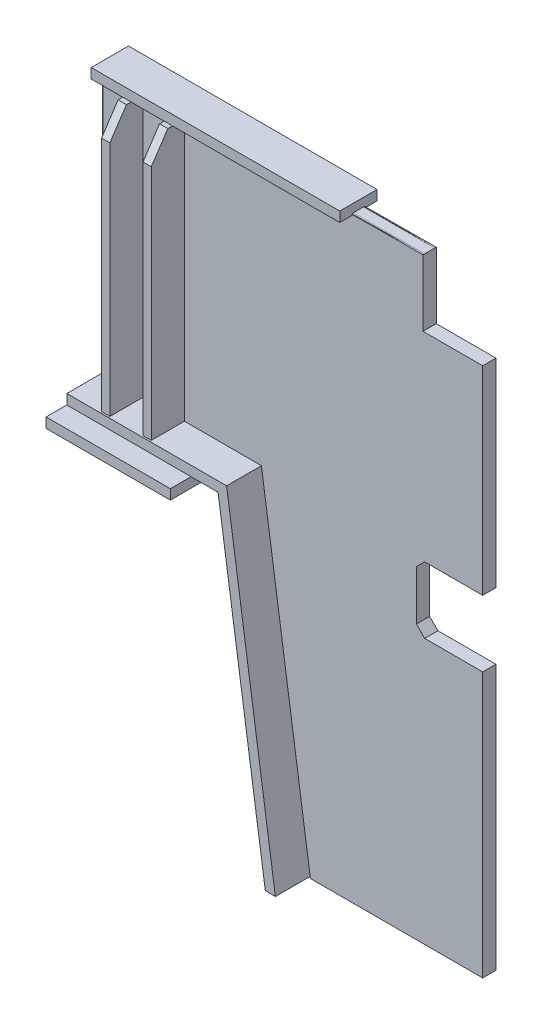
SolidWorks part; units mm, degrees
ref_plane "前视" through (0, 0, 0) normal (0, 0, 1) x (1, 0, 0)
ref_plane "上视" through (0, 0, 0) normal (0, 1, 0) x (1, 0, 0)
ref_plane "右视" through (0, 0, 0) normal (1, 0, 0) x (0, 0, -1)
sketch "草图1" plane through (0, 0, 0) normal (0, 0, 1) x (1, 0, 0)
  line L0 (0, -320) -> (-70, -320)
  line L1 (-72, 0) -> (-460, 0)
  line L2 (-40, 116.6722) -> (-40, -759.2574) construction
  line L3 (0, -720) -> (-210, -720)
  line L4 (-460, 0) -> (-460, -320)
  line L5 (-80, -330) -> (-80, -390)
  line L6 (-70, -400) -> (0, -400)
  line L7 (0, -400) -> (0, -720)
  line L8 (-112, 271.0914) -> (-112, -671.0914) construction
  line L9 (-775.8996, -110) -> (-214.577, -110) construction
  line L15 (-210, -720) -> (-259.124, -327.0077)
  line L16 (-460, -320) -> (-267.0623, -320)
  line L17 (-72, 0) -> (-72, -80)
  line L18 (-72, -80) -> (0, -80)
  line L19 (0, -80) -> (0, -320)
  arc A0 (-80, -330) -> (-70, -320) centre (-70, -330) cw
  arc A1 (-70, -400) -> (-80, -390) centre (-70, -390) cw
  circle A2 centre (-112, -40) radius 13
  circle A3 centre (-112, -120) radius 13
  circle A4 centre (-112, -200) radius 13
  circle A5 centre (-112, -280) radius 13
  circle A6 centre (-40, -160) radius 13
  circle A7 centre (-40, -240) radius 13
  circle A8 centre (-40, -680) radius 13
  circle A9 centre (-40, -600) radius 13
  circle A10 centre (-40, -520) radius 13
  arc A11 (-259.124, -327.0077) -> (-267.0623, -320) centre (-267.0623, -328) ccw
  circle A12 centre (-112, -640) radius 13
  circle A13 centre (-112, -560) radius 13
  circle A14 centre (-112, -480) radius 13
  circle A15 centre (-260, -110) radius 37.5
  point P11 (-80, -320)
  point P49 (-260, -320)
  dimension "D4" = 10
  dimension "D5" = 10
  dimension "D13" = 72
  dimension "D14" = 80
  dimension "D18" = 72
  dimension "D20" = 80
  dimension "D24" = 8
  dimension "D25" = 40
  dimension "D26" = 40
  dimension "D32" = 26
  dimension "D34" = 75
  dimension "D3" = 80
  dimension "D6" = 720
  dimension "D7" = 72
  dimension "D8" = 320
  dimension "D9" = 320
  dimension "D10" = 460
  dimension "D11" = 80
  dimension "D12" = 40
  dimension "D15" = 40
  dimension "D16" = 80
  dimension "D17" = 80
  dimension "D19" = 80
  dimension "D21" = 210
  dimension "D22" = 392.9923
  dimension "D23" = 40
  dimension "D27" = 80
  dimension "D28" = 80
  dimension "D29" = 40
  dimension "D30" = 80
  dimension "D31" = 80
  dimension "D33" = 110
  dimension "D35" = 200
extrude "基体-拉伸" add sketch "草图1" along normal blind 16
fillet "圆角1" radius 2 28 edges at (-105, -720, 16) (0, -560, 16) (-35, -400, 16) (-77.0711, -397.0711, 16) (-80, -360, 16) (-77.0711, -322.9289, 16) (-35, -320, 16) (0, -200, 16) (-36, -80, 16) (-99, -40, 16) (-72, -40, 16) (-261.7678, -322.0026, 16) (-266, 0, 16) (-99, -120, 16) (-460, -160, 16) (-99, -200, 16) (-363.5311, -320, 16) (-99, -280, 16) (-27, -160, 16) (-27, -240, 16) (-27, -680, 16) (-27, -600, 16) (-27, -520, 16) (-234.562, -523.5039, 16) (-99, -640, 16) (-99, -560, 16) (-99, -480, 16) (-222.5, -110, 16)
fillet "圆角2" radius 2 28 edges at (-363.5311, -320, 0) (-460, -160, 0) (-266, 0, 0) (-72, -40, 0) (-36, -80, 0) (0, -200, 0) (-35, -320, 0) (-77.0711, -322.9289, 0) (-80, -360, 0) (-77.0711, -397.0711, 0) (-35, -400, 0) (0, -560, 0) (-105, -720, 0) (-234.562, -523.5039, 0) (-261.7678, -322.0026, 0) (-99, -40, 0) (-99, -120, 0) (-99, -200, 0) (-99, -280, 0) (-27, -160, 0) (-27, -240, 0) (-27, -680, 0) (-27, -600, 0) (-27, -520, 0) (-99, -640, 0) (-99, -560, 0) (-99, -480, 0) (-222.5, -110, 0)
sketch "草图3" plane through (0, 0, 16) normal (0, 0, 1) x (1, 0, 0)
  line L0 (-74, -2) -> (-458, -2) construction
  line L1 (-420, -2) -> (-410, -2)
  line L2 (-420, -2) -> (-420, -318)
  line L3 (-420, -318) -> (-410, -318)
  line L4 (-410, -2) -> (-410, -318)
  line L5 (-458, -318) -> (-267.0623, -318) construction
  line L6 (-460, -320) -> (-460, 0) construction
  line L7 (-370, -2) -> (-360, -2)
  line L8 (-370, -2) -> (-370, -318)
  line L9 (-370, -318) -> (-360, -318)
  line L10 (-360, -2) -> (-360, -318)
  dimension "D1" = 10
  dimension "D2" = 10
  dimension "D3" = 40
  dimension "D4" = 40
extrude "凸台-拉伸2" add sketch "草图3" along normal blind 40 and the other way blind 56
sketch "草图4" plane through (-420, 0, 0) normal (-1, 0, 0) x (0, 0, 1)
  line L0 (-20, -2) -> (-45.5, -32)
  line L1 (0, -2) -> (-40, -2) construction
  line L3 (-20, -2) -> (-45.5, -2)
  line L4 (-45.5, -2) -> (-45.5, -32)
  dimension "D1" = 30
  dimension "D2" = 25.5
extrude "切除-拉伸1" cut sketch "草图4" against normal through all
sketch "草图5" plane through (-420, 0, 0) normal (-1, 0, 0) x (0, 0, 1)
  line L0 (36, -2) -> (56, -32)
  line L1 (56, -2) -> (16, -2) construction
  line L2 (56, -2) -> (56, -318) construction
  line L3 (36, -2) -> (56, -2)
  line L4 (56, -2) -> (56, -32)
  dimension "D1" = 30
extrude "切除-拉伸2" cut sketch "草图5" against normal through all
sketch "草图6" plane through (0, 0, 16) normal (0, 0, 1) x (1, 0, 0)
  line L0 (-460, -320) -> (-460, 0) construction
  line L1 (-267.0623, -318) -> (-460, -318)
  line L2 (-267.0623, -318) -> (-208.2344, -718)
  line L3 (-277.4265, -330) -> (-460, -330)
  line L4 (-460, -318) -> (-460, -330)
  line L6 (-277.4265, -330) -> (-220.3635, -718)
  line L7 (-220.3635, -718) -> (-208.2344, -718)
  dimension "D1" = 12
  dimension "D2" = 12
extrude "凸台-拉伸5" add sketch "草图6" along normal blind 42 and the other way blind 58
sketch "草图7" plane through (0, 0, 0) normal (0, 0, -1) x (-1, 0, 0)
  line L1 (458, -2) -> (158, -2)
  line L2 (458, -2) -> (458, 10)
  line L3 (458, 10) -> (158, 10)
  line L4 (158, -2) -> (158, 10)
  dimension "D1" = 300
  dimension "D2" = 12
extrude "凸台-拉伸6" add sketch "草图7" along normal blind 14.5 and the other way blind 30.5
sketch "草图8" plane through (0, -330, 0) normal (0, -1, 0) x (1, 0, 0)
  line L0 (-515.842, 8) -> (-234.809, 8) construction
  line L1 (-460, -42) -> (-277.4265, -42) construction
  line L2 (-460, 58) -> (-277.4265, 58) construction
  line L4 (-310, 83) -> (-460, 83)
  line L5 (-310, 83) -> (-310, -67)
  line L6 (-310, -67) -> (-460, -67)
  line L7 (-460, 83) -> (-460, -67)
  line L8 (-460, 58) -> (-460, -42) construction
  dimension "D1" = 150
  dimension "D2" = 150
extrude "凸台-拉伸7" add sketch "草图8" along normal blind 12
sketch "草图9" plane through (0, 0, 16) normal (0, 0, 1) x (1, 0, 0)
  line L0 (0, -720) -> (0, -400)
  line L1 (0, -400) -> (-70, -400)
  line L3 (-70, -320) -> (0, -320)
  line L4 (0, -320) -> (0, -80)
  line L5 (0, -80) -> (-72, -80)
  line L6 (-72, -80) -> (-72, 0)
  line L7 (-72, 0) -> (-360, -2)
  line L8 (-360, -2) -> (-360, -318)
  line L9 (-360, -318) -> (-267.0623, -318)
  line L10 (-267.0623, -318) -> (-207.9403, -720)
  line L14 (-70, -400) -> (0, -400) construction
  line L16 (-70, -400) -> (-80, -390)
  line L17 (-80, -390) -> (-80, -330)
  line L18 (-80, -330) -> (-70, -320)
  line L19 (-70, -318) -> (-70, -320) construction
  line L20 (-267.0623, -318) -> (-460, -318) construction
  line L21 (-208.2344, -718) -> (-267.0623, -318) construction
  line L22 (-207.9403, -720) -> (0, -720)
  line L23 (0, -720) -> (-210, -720) construction
extrude "凸台-拉伸8" add sketch "草图9" against normal blind 16
